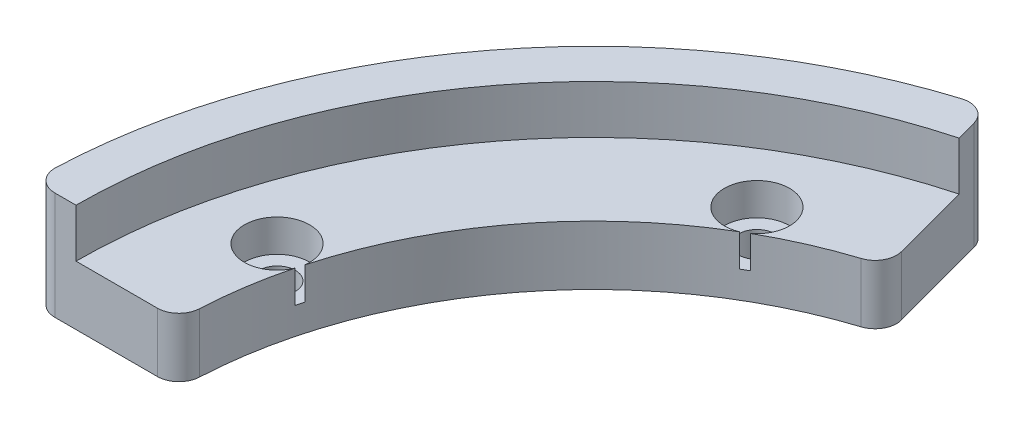
SolidWorks part; units mm, degrees
ref_plane "Спереди" through (0, 0, 0) normal (0, 0, 1) x (1, 0, 0)
ref_plane "Сверху" through (0, 0, 0) normal (0, 1, 0) x (1, 0, 0)
ref_plane "Справа" through (0, 0, 0) normal (1, 0, 0) x (0, 0, -1)
sketch "Эскиз1" plane through (0, 0, 0) normal (0, 0, 1) x (1, 0, 0)
  line L0 (-52, 0) -> (-38.5, 0)
  line L1 (-38.5, 0) -> (-38.5, 5.5)
  line L2 (-38.5, 5.5) -> (-48, 5.5)
  line L3 (-48, 5.5) -> (-48, 10)
  line L4 (-48, 10) -> (-52, 10)
  line L5 (-52, 10) -> (-52, 0)
  line L6 (0, 0) -> (0, 10) construction
revolve "Повернуть1" add sketch "Эскиз1" angle 75 about L6
hole_wizard "Цековка для винта с заклепочной головкой M31" positions "Эскиз3" profile "Эскиз2" counterbore size "M3" standard "Ansi Metric"
sketch "Эскиз3" plane through (0, 5.5, 0) normal (0, 1, 0) x (1, 0, 0)
  point P0 (-20.75, 35.9401)
  point P1 (-40.0859, 10.741)
sketch "Эскиз2" plane through (-20.75, 5.5, -35.9401) normal (1, 0, 0) x (0, 0, 1)
  line L0 (0, 0) -> (0, 5.5)
  line L1 (0, 5.5) -> (1.7, 5.5)
  line L3 (1.7, 5.5) -> (1.7, 3)
  line L4 (1.7, 3) -> (3.025, 3)
  line L5 (3.025, 3) -> (3.025, 0)
  line L7 (3.025, 0) -> (0, 0)
  line L11 (0, -6.35) -> (0, 107.95) construction
  dimension "Диаметр сквозного отверстия" = 3.4
  dimension "Глубина сквозного отверстия" = 5.5
  dimension "Диаметр цековки" = 6.05
  dimension "Глубина цековки" = 3
fillet "Скругление1" radius 2 4 edges at (-13.4586, 5, -50.2281) (-9.9645, 2.75, -37.1881) (-52, 5, 0) (-38.5, 2.75, 0)
